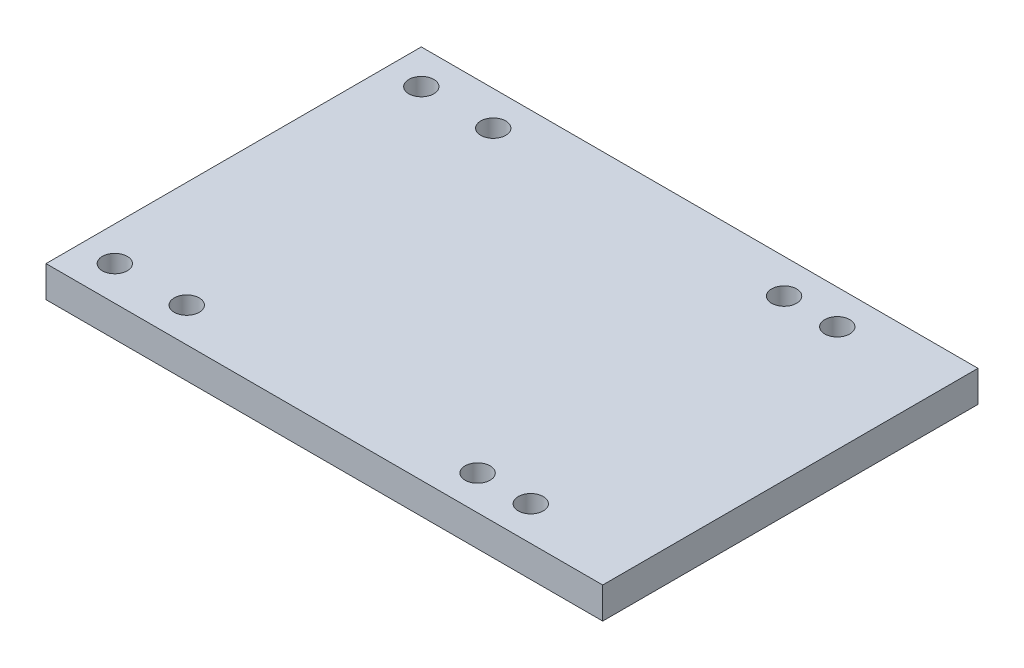
SolidWorks part; units mm, degrees
ref_plane "前视基准面" through (0, 0, 0) normal (0, 0, 1) x (1, 0, 0)
ref_plane "上视基准面" through (0, 0, 0) normal (0, 1, 0) x (1, 0, 0)
ref_plane "右视基准面" through (0, 0, 0) normal (1, 0, 0) x (0, 0, -1)
sketch "草图1" plane through (0, 0, 0) normal (0, 1, 0) x (1, 0, 0)
  line L0 (-20.0892, 15.8736) -> (-20.0892, -33.1264) construction
  line L1 (-37.0892, 21.3736) -> (51.9108, 21.3736)
  line L2 (-37.0892, 21.3736) -> (-37.0892, -38.6264)
  line L3 (-37.0892, -38.6264) -> (51.9108, -38.6264)
  line L4 (51.9108, 21.3736) -> (51.9108, -38.6264)
  line L5 (-31.5892, 15.8736) -> (26.4108, 15.8736) construction
  line L6 (-31.5892, 15.8736) -> (-31.5892, -33.1264) construction
  line L7 (-31.5892, -33.1264) -> (26.4108, -33.1264) construction
  line L8 (26.4108, 15.8736) -> (26.4108, -33.1264) construction
  line L9 (34.9108, 15.8736) -> (34.9108, -33.1264) construction
  line L10 (-20.0892, -8.6264) -> (34.9108, -8.6264) construction
  circle A0 centre (-31.5892, 15.8736) radius 2
  circle A1 centre (26.4108, 15.8736) radius 2
  circle A2 centre (-31.5892, -33.1264) radius 2
  circle A3 centre (26.4108, -33.1264) radius 2
  circle A4 centre (-20.0892, 15.8736) radius 2
  circle A5 centre (34.9108, 15.8736) radius 2
  circle A6 centre (-20.0892, -33.1264) radius 2
  circle A7 centre (34.9108, -33.1264) radius 2
  point P8 (-37.0892, -8.6264)
  point P9 (-31.5892, -8.6264)
  point P20 (7.4108, -8.6264)
  point P21 (7.4108, 21.3736)
  dimension "D5" = 5.5
  dimension "D1" = 60
  dimension "D2" = 89
  dimension "D3" = 58
  dimension "D4" = 49
  dimension "D6" = 55
extrude "凸台-拉伸1" add sketch "草图1" along normal blind 5
